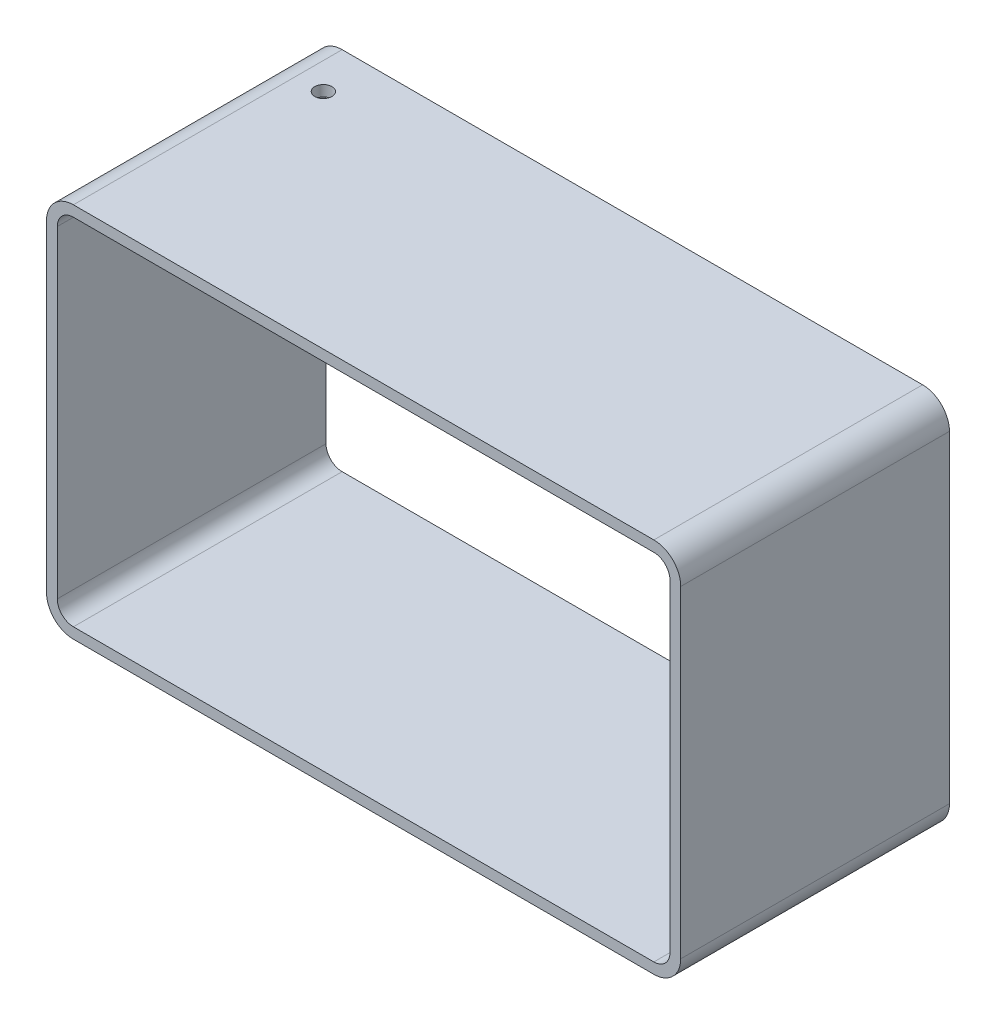
SolidWorks part; units mm, degrees
ref_plane "正面" through (0, 0, 0) normal (0, 0, 1) x (1, 0, 0)
ref_plane "平面" through (0, 0, 0) normal (0, 1, 0) x (1, 0, 0)
ref_plane "右側面" through (0, 0, 0) normal (1, 0, 0) x (0, 0, -1)
sketch "ｽｹｯﾁ1" plane through (0, 0, 0) normal (0, 0, 1) x (1, 0, 0)
  line L1 (-59, -35) -> (59, -35)
  line L2 (-59, -35) -> (-59, 35)
  line L3 (-59, 35) -> (59, 35)
  line L4 (59, -35) -> (59, 35)
  line L5 (-59, -35) -> (59, 35) construction
  line L6 (-59, 35) -> (59, -35) construction
  point P0 (0, 0)
  dimension "D1" = 118
  dimension "D2" = 70
extrude "ﾎﾞｽ - 押し出し1" add sketch "ｽｹｯﾁ1" along normal blind 50
fillet "ﾌｨﾚｯﾄ1" radius 5 4 edges at (59, -35, 25) (-59, -35, 25) (-59, 35, 25) (59, 35, 25)
sketch "ｽｹｯﾁ2" plane through (0, 0, 50) normal (0, 0, 1) x (1, 0, 0)
  line L8 (-54, -33) -> (54, -33)
  line L9 (57, -30) -> (57, 30)
  line L10 (54, 33) -> (-54, 33)
  line L11 (-57, 30) -> (-57, -30)
  line L12 (-54, -33) -> (54, -33)
  line L13 (57, -30) -> (57, 30)
  line L14 (54, 33) -> (-54, 33)
  line L15 (-57, 30) -> (-57, -30)
  arc A8 (54, -33) -> (57, -30) centre (54, -30) ccw
  arc A9 (57, 30) -> (54, 33) centre (54, 30) ccw
  arc A10 (-54, 33) -> (-57, 30) centre (-54, 30) ccw
  arc A11 (-57, -30) -> (-54, -33) centre (-54, -30) ccw
  arc A12 (54, -33) -> (57, -30) centre (54, -30) ccw
  arc A13 (57, 30) -> (54, 33) centre (54, 30) ccw
  arc A14 (-54, 33) -> (-57, 30) centre (-54, 30) ccw
  arc A15 (-57, -30) -> (-54, -33) centre (-54, -30) ccw
  dimension "D1" = 2
extrude "ｶｯﾄ - 押し出し1" cut sketch "ｽｹｯﾁ2" against normal through all
sketch "ｽｹｯﾁ3" plane through (0, -35, 0) normal (0, -1, 0) x (1, 0, 0)
  line L0 (-54, 0) -> (54, 0) construction
  line L1 (54, 0) -> (54, 50) construction
  circle A0 centre (49, 8.5) radius 1.6
  dimension "D1" = 8.5
  dimension "D2" = 5
  dimension "D3" = 3.2
extrude "ｶｯﾄ - 押し出し2" cut sketch "ｽｹｯﾁ3" against normal up to next
sketch "ｽｹｯﾁ4" plane through (0, 35, 0) normal (0, 1, 0) x (1, 0, 0)
  line L0 (54, 0) -> (-54, 0) construction
  line L1 (-54, 0) -> (-54, -50) construction
  circle A0 centre (-49, -8.5) radius 1.6
  dimension "D1" = 8.5
  dimension "D2" = 5
  dimension "D3" = 3.2
extrude "ｶｯﾄ - 押し出し3" cut sketch "ｽｹｯﾁ4" against normal blind 50
